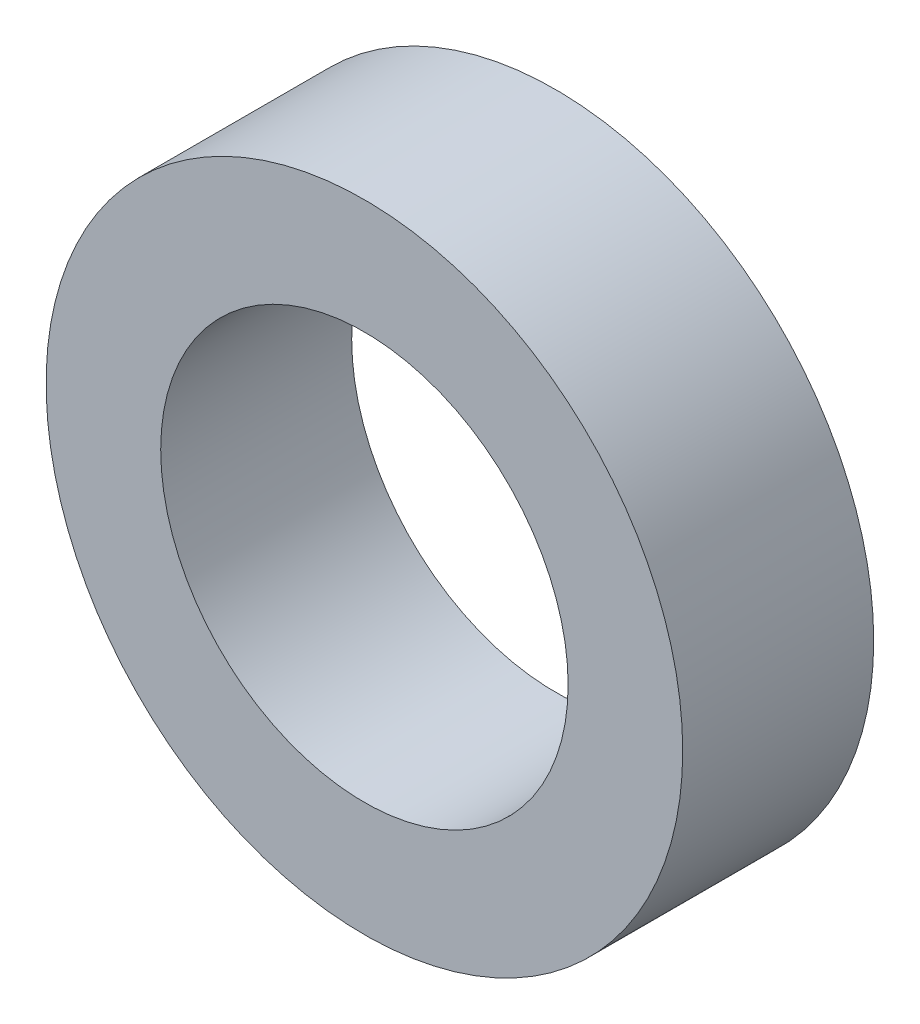
SolidWorks part; units mm, degrees
other "Rear Spring Spacer"
ref_plane "Front Plane" through (0, 0, 0) normal (0, 0, 1) x (1, 0, 0)
ref_plane "Top Plane" through (0, 0, 0) normal (0, 1, 0) x (1, 0, 0)
ref_plane "Right Plane" through (0, 0, 0) normal (1, 0, 0) x (0, 0, -1)
sketch3d "Eyelet spacer outside sketch datum points"
  point P0 (35.7083, -12, 11)
  point P1 (45.7083, -12, 11)
  point P2 (35.7083, -2, 11)
ref_plane "Eyelet spacer outside sketch plane" through (0, 0, 11) normal (0, 0, 1) x (1, 0, 0)
sketch "Eyelet spacer outside sketch" plane through (0, 0, 11) normal (0, 0, 1) x (1, 0, 0)
  circle A0 centre (35.7083, -12) radius 2.5
extrude "Eyelet spacer outside" add sketch "Eyelet spacer outside sketch" along normal blind 1.5 separate body
sketch3d "Eyelet spacer bore sketch datum points"
  point P0 (35.7083, -12, 10.9)
  point P1 (45.7083, -12, 10.9)
  point P2 (35.7083, -2, 10.9)
ref_plane "Eyelet spacer bore sketch plane" through (0, 0, 10.9) normal (0, 0, 1) x (1, 0, 0)
sketch "Eyelet spacer bore sketch" plane through (0, 0, 10.9) normal (0, 0, 1) x (1, 0, 0)
  circle A0 centre (35.7083, -12) radius 1.6
extrude "Eyelet spacer bore" cut sketch "Eyelet spacer bore sketch" along normal blind 1.7
